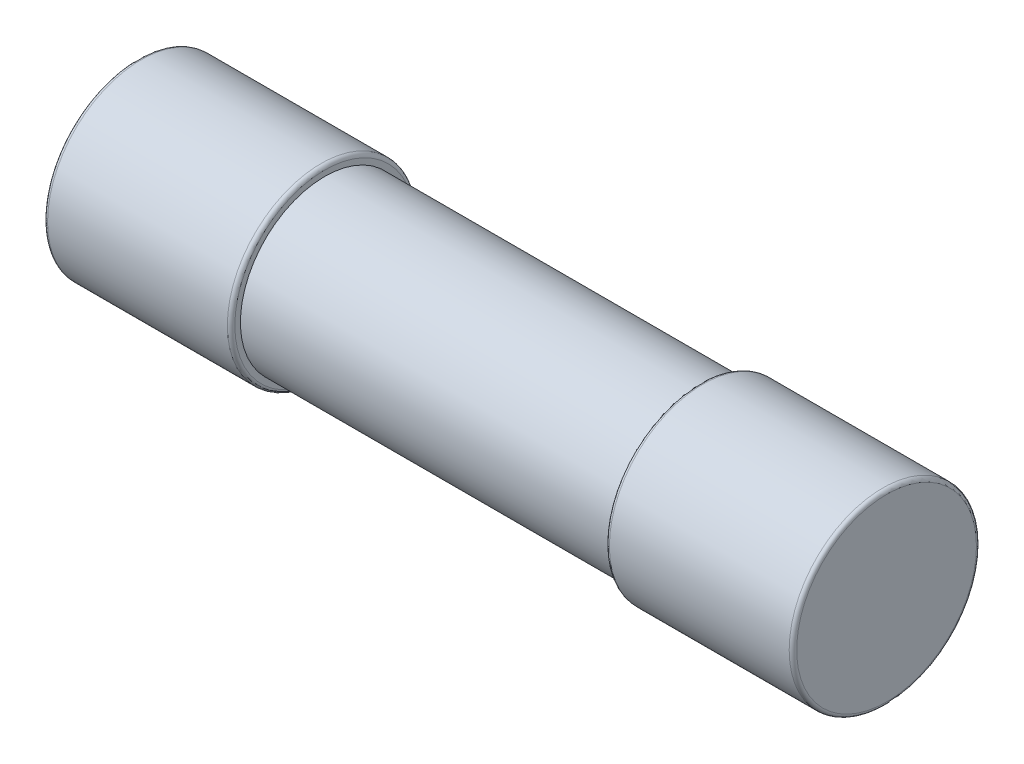
SolidWorks part; units mm, degrees
material "AISI 304"
ref_plane "Piano frontale" through (0, 0, 0) normal (0, 0, 1) x (1, 0, 0)
ref_plane "Piano superiore" through (0, 0, 0) normal (0, 1, 0) x (1, 0, 0)
ref_plane "Piano destro" through (0, 0, 0) normal (1, 0, 0) x (0, 0, -1)
sketch "Schizzo4" plane through (0, 0, 0) normal (0, 0, 1) x (1, 0, 0)
  line L0 (0, 0) -> (-9.75, 0) construction
  line L1 (-9.75, 0) -> (-9.75, 2.25)
  line L2 (-9.75, 2.25) -> (9.75, 2.25)
  line L3 (9.75, 2.25) -> (9.75, 0)
  line L4 (9.75, 0) -> (0, 0) construction
  line L5 (-9.75, 2) -> (9.75, 2)
  dimension "D1" = 19.5
  dimension "D2" = 2.25
  dimension "D3" = 0.25
revolve "Rivoluzione3" add sketch "Schizzo4" angle 360 about L0
sketch "Schizzo6" plane through (0, 0, 0) normal (0, 0, 1) x (1, 0, 0)
  line L0 (9.75, 0) -> (-9.75, 0)
  line L1 (-9.75, 2.25) -> (-9.75, -2.25) construction
  line L2 (-9.75, 0) -> (-10, 0)
  line L3 (-10, 0) -> (-10, 2.5)
  line L4 (-10, 2.5) -> (-5, 2.5)
  line L5 (-5, 2.5) -> (-5, 2.25)
  line L6 (9.75, 2.25) -> (-9.75, 2.25) construction
  line L7 (-5, 2.25) -> (-9.75, 2.25)
  line L8 (-9.75, 2.25) -> (-9.75, 0.1)
  line L9 (-9.75, 0.1) -> (9.75, 0.1)
  line L10 (0, 0.1) -> (0, 0)
  line L11 (0, 0) -> (0, -2.25) construction
  line L12 (-9.75, -2.25) -> (9.75, -2.25) construction
  line L13 (9.75, 2.25) -> (9.75, 0.1)
  line L14 (5, 2.25) -> (9.75, 2.25)
  line L15 (5, 2.5) -> (5, 2.25)
  line L16 (10, 2.5) -> (5, 2.5)
  line L17 (10, 0) -> (10, 2.5)
  line L18 (9.75, 0) -> (10, 0)
  dimension "D1" = 0.25
  dimension "D2" = 5
  dimension "D3" = 2.5
  dimension "D4" = 0.1
revolve "Rivoluzione4" add sketch "Schizzo6" angle 360 about L0
fillet "Raccordo1" radius 0.1 4 edges at (-10, 0, -2.5) (-5, 0, -2.5) (10, 0, -2.5) (5, 0, -2.5)
